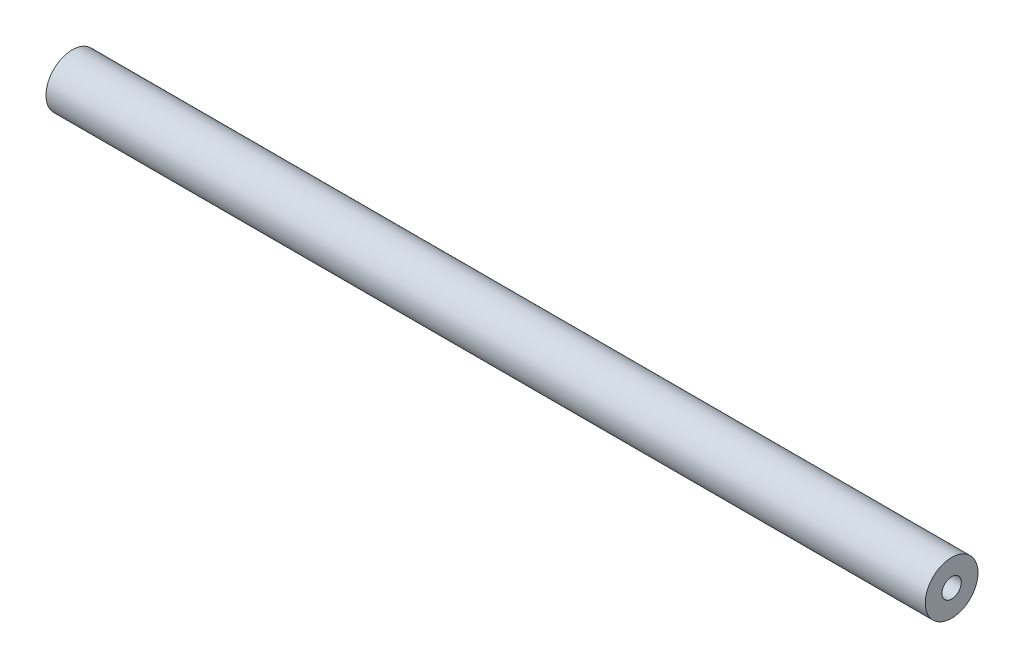
SolidWorks part; units mm, degrees
material "6061-T6 (SS)"
ref_plane "前视基准面" through (0, 0, 0) normal (0, 0, 1) x (1, 0, 0)
ref_plane "上视基准面" through (0, 0, 0) normal (0, 1, 0) x (1, 0, 0)
ref_plane "右视基准面" through (0, 0, 0) normal (1, 0, 0) x (0, 0, -1)
other "Configuration Table"
sketch "草图1" plane through (0, 0, 0) normal (1, 0, 0) x (0, 0, -1)
  circle A0 centre (0, 0) radius 1.65
  circle A1 centre (0, 0) radius 4.5
  dimension "D1" = 3.3
  dimension "D2" = 9
extrude "凸台-拉伸1" add sketch "草图1" along normal blind 150
